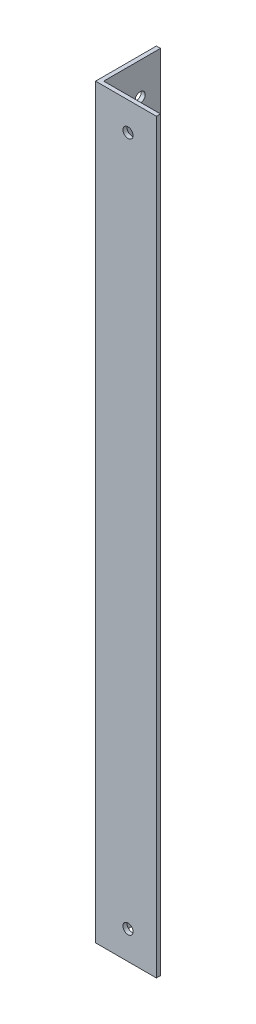
SolidWorks part; units mm, degrees
ref_plane "正面" through (0, 0, 0) normal (0, 0, 1) x (1, 0, 0)
ref_plane "平面" through (0, 0, 0) normal (0, 1, 0) x (1, 0, 0)
ref_plane "右側面" through (0, 0, 0) normal (1, 0, 0) x (0, 0, -1)
sketch "ｽｹｯﾁ1" plane through (0, 0, 0) normal (0, 1, 0) x (1, 0, 0)
  line L1 (0, 0) -> (15, 0)
  line L2 (0, 0) -> (0, -1)
  line L3 (0, -1) -> (15, -1)
  line L4 (15, 0) -> (15, -1)
  dimension "D1" = 15
  dimension "D2" = 1
sketch "ｽｹｯﾁ2" plane through (0, 0, 0) normal (0, 1, 0) x (1, 0, 0)
extrude "ﾎﾞｽ - 押し出し1" add sketch "ｽｹｯﾁ1" along normal blind 184
sketch "ｽｹｯﾁ3" plane through (0, 0, 0) normal (0, 0, -1) x (-1, 0, 0)
  line L1 (0, 184) -> (-1, 184)
  line L2 (0, 184) -> (0, 0)
  line L3 (0, 0) -> (-1, 0)
  line L4 (-1, 184) -> (-1, 0)
  dimension "D1" = 1
  dimension "D2" = 184
extrude "ﾎﾞｽ - 押し出し2" add sketch "ｽｹｯﾁ3" along normal blind 14
hole_wizard "M3x0.5 ねじ穴1" positions "ｽｹｯﾁ4" profile "ｽｹｯﾁ5" tap size "M3x0.5" standard "JIS" end condition through all
sketch "ｽｹｯﾁ4" plane through (0, 0, 0) normal (-1, 0, 0) x (0, 0, 1)
  line L0 (-14, 184) -> (1, 184) construction
  line L1 (-14, 0) -> (-14, 184) construction
  line L2 (8.25, 0) -> (-8.25, 0) construction
  point P0 (-9, 8)
  point P2 (-9, 176)
  dimension "D1" = 8
  dimension "D2" = 5
  dimension "D3" = 5
  dimension "D4" = 8
sketch "ｽｹｯﾁ5" plane through (0, 8, -9) normal (0, 1, 0) x (0, 0, 1)
  line L0 (0, 0) -> (0, 15)
  line L1 (0, 15) -> (1.25, 15)
  line L2 (1.25, 15) -> (1.25, 0)
  line L5 (1.25, 0) -> (0, 0)
  line L11 (0, -6.35) -> (0, 107.95) construction
  dimension "次ｻｰﾌｪｽまでのねじ下穴ﾄﾞﾘﾙ直径" = 2.5
  dimension "次ｻｰﾌｪｽまでのねじ下穴ﾄﾞﾘﾙの深さ" = 15
cosmetic thread "穴のねじ山1" parameters "D2"=3
cosmetic thread "穴のねじ山2" parameters "D2"=3
hole_wizard "M3x0.5 ねじ穴2" positions "ｽｹｯﾁ6" profile "ｽｹｯﾁ7" tap size "M3x0.5" standard "JIS" end condition through all
sketch "ｽｹｯﾁ6" plane through (0, 0, 1) normal (0, 0, 1) x (1, 0, 0)
  line L0 (15, 184) -> (15, 0) construction
  line L1 (8.25, 0) -> (-8.25, 0) construction
  line L2 (0, 184) -> (15, 184) construction
  point P0 (8, 7)
  point P2 (8, 177)
  dimension "D1" = 7
  dimension "D2" = 7
  dimension "D3" = 7
  dimension "D4" = 7
sketch "ｽｹｯﾁ7" plane through (8, 7, 1) normal (1, 0, 0) x (0, -1, 0)
  line L0 (0, 0) -> (0, 15)
  line L1 (0, 15) -> (1.25, 15)
  line L2 (1.25, 15) -> (1.25, 0)
  line L5 (1.25, 0) -> (0, 0)
  line L11 (0, -6.35) -> (0, 107.95) construction
  dimension "次ｻｰﾌｪｽまでのねじ下穴ﾄﾞﾘﾙ直径" = 2.5
  dimension "次ｻｰﾌｪｽまでのねじ下穴ﾄﾞﾘﾙの深さ" = 15
cosmetic thread "穴のねじ山3" parameters "D2"=3
cosmetic thread "穴のねじ山4" parameters "D2"=3
